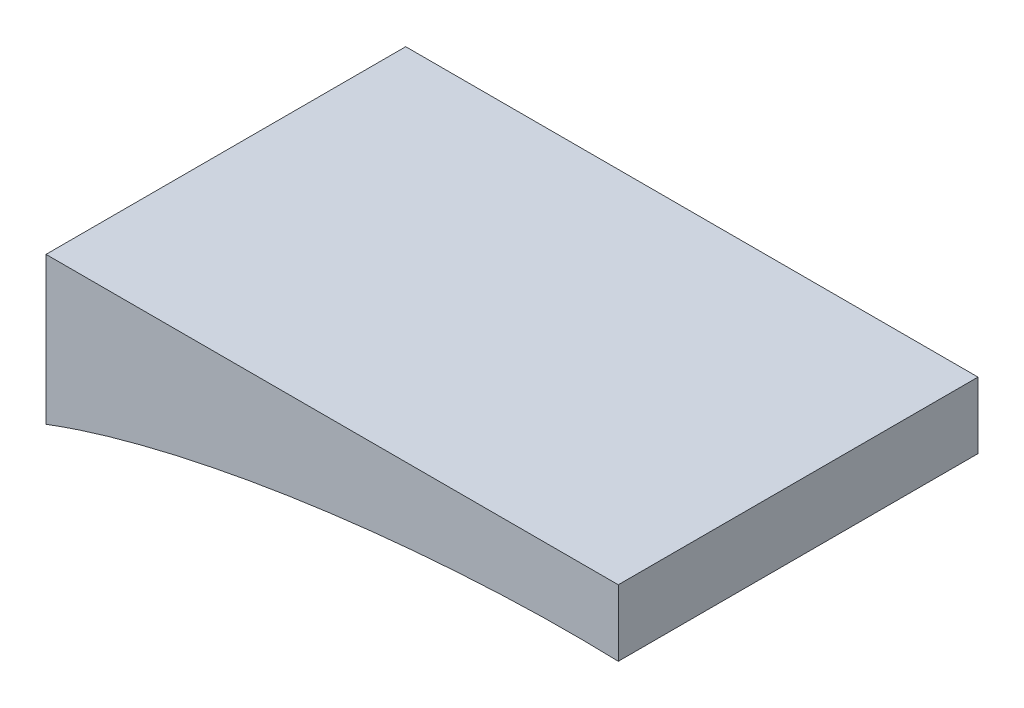
SolidWorks part; units mm, degrees
ref_plane "Front Plane" through (0, 0, 0) normal (0, 0, 1) x (1, 0, 0)
ref_plane "Top Plane" through (0, 0, 0) normal (0, 1, 0) x (1, 0, 0)
ref_plane "Right Plane" through (0, 0, 0) normal (1, 0, 0) x (0, 0, -1)
curve "Curve1"
  spline degree 3 poles (99.2573, 0.1883, 0) (100.1824, -0.0489, 0) (99.2961, 0.1993, 0) (98.6191, 0.462, 0) (97.0519, 1.0473, 0) (95.2309, 1.7549, 0) (92.9378, 2.5568, 0) (90.2536, 3.3336, 0) (87.1477, 4.0816, 0) (83.6535, 4.8449, 0) (79.8051, 5.6126, 0) (75.6551, 6.3782, 0) (71.2568, 7.1284, 0) (66.6666, 7.8484, 0) (61.9423, 8.5212, 0) (57.142, 9.1269, 0) (52.3233, 9.6447, 0) (47.5422, 10.0467, 0) (42.8474, 10.3157, 0) (38.2509, 10.3642, 0) (33.7665, 10.1859, 0) (29.4045, 9.86, 0) (25.2057, 9.3963, 0) (21.2146, 8.8145, 0) (17.4732, 8.1296, 0) (14.0211, 7.3557, 0) (10.8932, 6.51, 0) (8.1211, 5.6039, 0) (5.7296, 4.6586, 0) (3.7392, 3.6865, 0) (2.1629, 2.7162, 0) (1.0057, 1.7671, 0) (0.3099, 0.9241, 0) (0.0336, 0.3269, 0) (0.0006, 0.059, 0) (-0.0005, -0.0441, 0) (0.0087, -0.1472, 0) (0.0976, -0.2807, 0) (0.2176, -0.4056, 0) (0.6069, -0.7185, 0) (1.5156, -1.1239, 0) (3.0705, -1.583, 0) (5.1523, -2.0072, 0) (7.7279, -2.3917, 0) (10.7759, -2.7499, 0) (14.2511, -3.0772, 0) (18.0407, -3.4773, 0) (22.0414, -3.9067, 0) (26.2166, -4.1171, 0) (30.5565, -4.0983, 0) (35.1014, -3.8476, 0) (39.8555, -3.2929, 0) (44.8531, -2.5697, 0) (50.0777, -1.6972, 0) (55.4969, -0.8089, 0) (61.0345, 0.0244, 0) (66.5901, 0.7423, 0) (72.0549, 1.3013, 0) (77.3167, 1.6728, 0) (82.2608, 1.8417, 0) (86.7784, 1.812, 0) (90.7289, 1.5797, 0) (94.0476, 1.182, 0) (96.5243, 0.7715, 0) (98.476, 0.3569, 0) (99.2573, 0.1883, 0) (100.1824, -0.0489, 0) (99.2961, 0.1993, 0) knots -0.015875 -0.006971 -0.001726 0 0.001709 0.006655 0.014348 0.024259 0.036042 0.049641 0.065255 0.082793 0.102031 0.122721 0.144597 0.167375 0.190768 0.214483 0.238233 0.261741 0.284747 0.307088 0.329034 0.350455 0.371139 0.39089 0.409512 0.426831 0.442689 0.45695 0.469523 0.480322 0.48935 0.49658 0.502135 0.505254 0.506016 0.506063 0.506764 0.507486 0.508356 0.509304 0.514776 0.522722 0.53308 0.54584 0.560863 0.578018 0.596961 0.616675 0.636937 0.658148 0.680211 0.703561 0.728221 0.754164 0.781136 0.808649 0.836174 0.86317 0.889092 0.913409 0.935618 0.955187 0.97148 0.984125 0.993029 0.998274 1 1.001709 1.006655 1.014348 periodic
sketch "Sketch3" plane through (0, 0, 0) normal (0, 0, 1) x (1, 0, 0)
  line L0 (25, 2.7) -> (25, 9.3456) construction
  line L1 (7.5, 5.3454) -> (7.5, 14.3454)
  line L2 (7.5, 14.3454) -> (42.5, 14.3454)
  line L3 (42.5, 14.3454) -> (42.5, 10.2907)
  circle A0 centre (25, 2.7) radius 3 construction
  spline S0 degree 3 poles (99.2573, 0.1883) (100.1824, -0.0489) (99.2961, 0.1993) (98.6191, 0.462) (97.0519, 1.0473) (95.2309, 1.7549) (92.9378, 2.5568) (90.2536, 3.3336) (87.1477, 4.0816) (83.6535, 4.8449) (79.8051, 5.6126) (75.6551, 6.3782) (71.2568, 7.1284) (66.6666, 7.8484) (61.9423, 8.5212) (57.142, 9.1269) (52.3233, 9.6447) (47.5422, 10.0467) (42.8474, 10.3157) (38.2509, 10.3642) (33.7665, 10.1859) (29.4045, 9.86) (25.2057, 9.3963) (21.2146, 8.8145) (17.4732, 8.1296) (14.0211, 7.3557) (10.8932, 6.51) (8.1211, 5.6039) (5.7296, 4.6586) (3.7392, 3.6865) (2.1629, 2.7162) (1.0057, 1.7671) (0.3099, 0.9241) (0.0336, 0.3269) (0.0006, 0.059) (-0.0005, -0.0441) (0.0087, -0.1472) (0.0976, -0.2807) (0.2176, -0.4056) (0.6069, -0.7185) (1.5156, -1.1239) (3.0705, -1.583) (5.1523, -2.0072) (7.7279, -2.3917) (10.7759, -2.7499) (14.2511, -3.0772) (18.0407, -3.4773) (22.0414, -3.9067) (26.2166, -4.1171) (30.5565, -4.0983) (35.1014, -3.8476) (39.8555, -3.2929) (44.8531, -2.5697) (50.0777, -1.6972) (55.4969, -0.8089) (61.0345, 0.0244) (66.5901, 0.7423) (72.0549, 1.3013) (77.3167, 1.6728) (82.2608, 1.8417) (86.7784, 1.812) (90.7289, 1.5797) (94.0476, 1.182) (96.5243, 0.7715) (98.476, 0.3569) (99.2573, 0.1883) (100.1824, -0.0489) (99.2961, 0.1993) knots -0.015875 -0.006971 -0.001726 0 0.001709 0.006655 0.014348 0.024259 0.036042 0.049641 0.065255 0.082793 0.102031 0.122721 0.144597 0.167375 0.190768 0.214483 0.238233 0.261741 0.284747 0.307088 0.329034 0.350455 0.371139 0.39089 0.409512 0.426831 0.442689 0.45695 0.469523 0.480322 0.48935 0.49658 0.502135 0.505254 0.506016 0.506063 0.506764 0.507486 0.508356 0.509304 0.514776 0.522722 0.53308 0.54584 0.560863 0.578018 0.596961 0.616675 0.636937 0.658148 0.680211 0.703561 0.728221 0.754164 0.781136 0.808649 0.836174 0.86317 0.889092 0.913409 0.935618 0.955187 0.97148 0.984125 0.993029 0.998274 1 1.001709 1.006655 1.014348 only from (100, 0) to (100, 0) construction
  spline S1 degree 3 poles (99.2573, 0.1883) (100.1824, -0.0489) (99.2961, 0.1993) (98.6191, 0.462) (97.0519, 1.0473) (95.2309, 1.7549) (92.9378, 2.5568) (90.2536, 3.3336) (87.1477, 4.0816) (83.6535, 4.8449) (79.8051, 5.6126) (75.6551, 6.3782) (71.2568, 7.1284) (66.6666, 7.8484) (61.9423, 8.5212) (57.142, 9.1269) (52.3233, 9.6447) (47.5422, 10.0467) (42.8474, 10.3157) (38.2509, 10.3642) (33.7665, 10.1859) (29.4045, 9.86) (25.2057, 9.3963) (21.2146, 8.8145) (17.4732, 8.1296) (14.0211, 7.3557) (10.8932, 6.51) (8.1211, 5.6039) (5.7296, 4.6586) (3.7392, 3.6865) (2.1629, 2.7162) (1.0057, 1.7671) (0.3099, 0.9241) (0.0336, 0.3269) (0.0006, 0.059) (-0.0005, -0.0441) (0.0087, -0.1472) (0.0976, -0.2807) (0.2176, -0.4056) (0.6069, -0.7185) (1.5156, -1.1239) (3.0705, -1.583) (5.1523, -2.0072) (7.7279, -2.3917) (10.7759, -2.7499) (14.2511, -3.0772) (18.0407, -3.4773) (22.0414, -3.9067) (26.2166, -4.1171) (30.5565, -4.0983) (35.1014, -3.8476) (39.8555, -3.2929) (44.8531, -2.5697) (50.0777, -1.6972) (55.4969, -0.8089) (61.0345, 0.0244) (66.5901, 0.7423) (72.0549, 1.3013) (77.3167, 1.6728) (82.2608, 1.8417) (86.7784, 1.812) (90.7289, 1.5797) (94.0476, 1.182) (96.5243, 0.7715) (98.476, 0.3569) (99.2573, 0.1883) (100.1824, -0.0489) (99.2961, 0.1993) knots -0.015875 -0.006971 -0.001726 0 0.001709 0.006655 0.014348 0.024259 0.036042 0.049641 0.065255 0.082793 0.102031 0.122721 0.144597 0.167375 0.190768 0.214483 0.238233 0.261741 0.284747 0.307088 0.329034 0.350455 0.371139 0.39089 0.409512 0.426831 0.442689 0.45695 0.469523 0.480322 0.48935 0.49658 0.502135 0.505254 0.506016 0.506063 0.506764 0.507486 0.508356 0.509304 0.514776 0.522722 0.53308 0.54584 0.560863 0.578018 0.596961 0.616675 0.636937 0.658148 0.680211 0.703561 0.728221 0.754164 0.781136 0.808649 0.836174 0.86317 0.889092 0.913409 0.935618 0.955187 0.97148 0.984125 0.993029 0.998274 1 1.001709 1.006655 1.014348 only from (100, 0) to (100, 0)
  dimension "D1" = 6
  dimension "D2" = 2.7
  dimension "D3" = 25
  dimension "D4" = 35
  dimension "D5" = 9
extrude "Boss-Extrude1" add sketch "Sketch3" along normal blind 22 contours S1 L3 L2 L1
